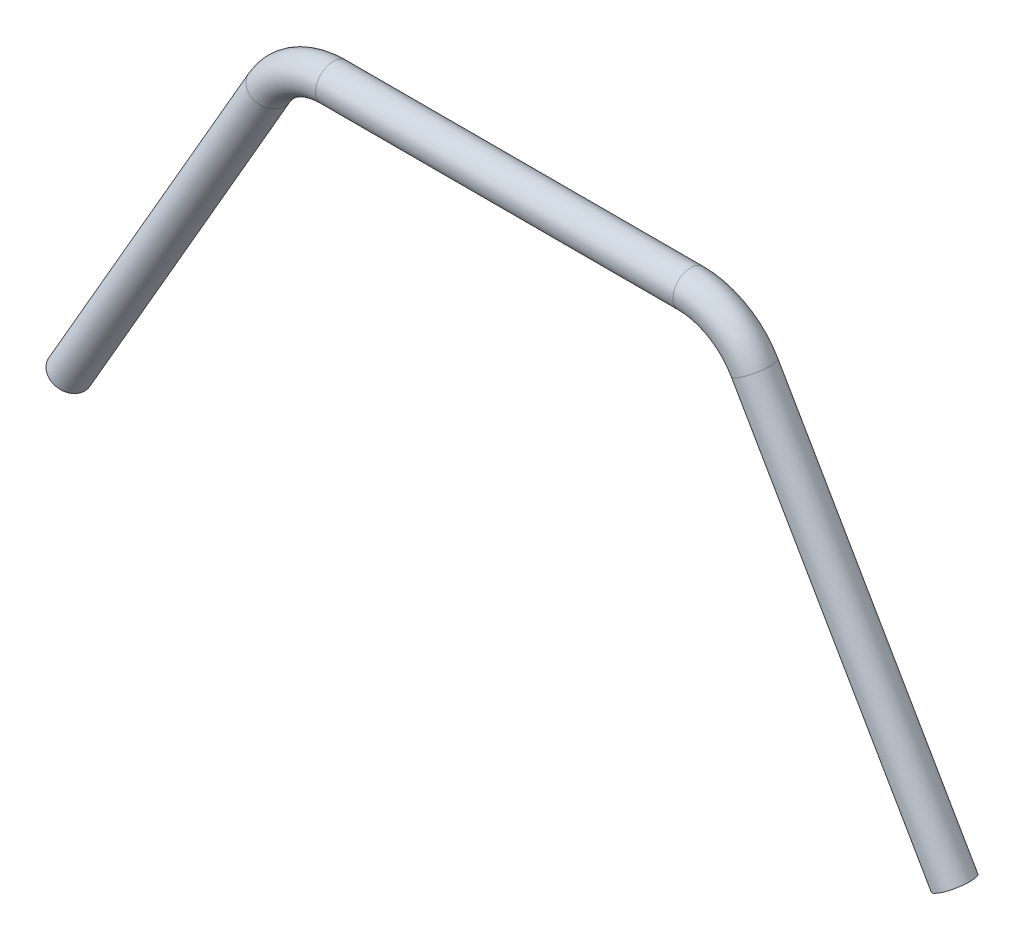
SolidWorks part; units mm, degrees
material "AISI 1020"
ref_plane "Спереди" through (0, 0, 0) normal (0, 0, 1) x (1, 0, 0)
ref_plane "Сверху" through (0, 0, 0) normal (0, 1, 0) x (1, 0, 0)
ref_plane "Справа" through (0, 0, 0) normal (1, 0, 0) x (0, 0, -1)
sketch "Эскиз1" plane through (0, 0, 0) normal (1, 0, 0) x (0, 0, -1)
  circle A0 centre (0, -6) radius 6
  dimension "D1" = 12
sketch "Эскиз2" plane through (0, 0, 0) normal (0, 0, 1) x (1, 0, 0)
  line L0 (0, -6) -> (60.5662, -6)
  line L1 (82.2169, -18.5) -> (150, -135.9038)
  line L3 (100, 0) -> (100, 16) construction
  arc A0 (60.5662, -6) -> (82.2169, -18.5) centre (60.5662, -31) cw
  point P10 (75, -6)
  dimension "D4" = 25
  dimension "D1" = 60
  dimension "D2" = 150
  dimension "D3" = 25
sweep "По траектории1" add profiles "Эскиз1" path "Эскиз2"
mirror "Зеркальное отражение1" about plane through (0, -6, 0) normal (1, 0, 0) of "По траектории1"
